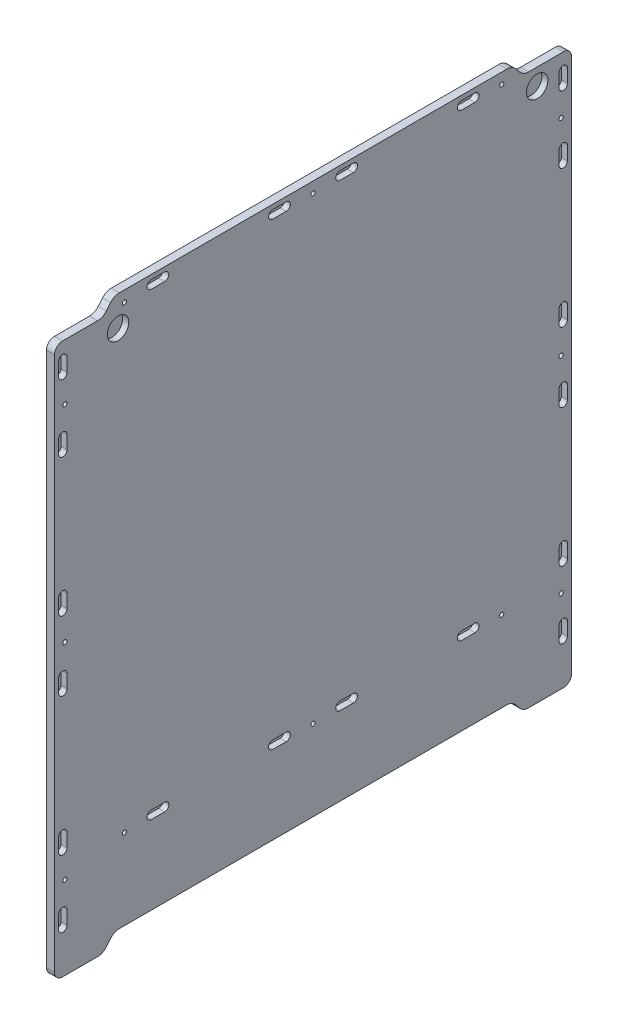
SolidWorks part; units mm, degrees
ref_plane "Alzado" through (0, 0, 0) normal (0, 0, 1) x (1, 0, 0)
ref_plane "Planta" through (0, 0, 0) normal (0, 1, 0) x (1, 0, 0)
ref_plane "Vista lateral" through (0, 0, 0) normal (1, 0, 0) x (0, 0, -1)
sketch "Croquis1" plane through (0, 0, 0) normal (1, 0, 0) x (0, 0, -1)
  line L0 (-15.4032, 213.9092) -> (-15.4032, -196.0905) construction
  line L1 (138.549, -203.0545) -> (135.2533, -199.1268)
  line L2 (171.0968, -206.0908) -> (145.0604, -206.0908)
  line L3 (177.0968, 198.0069) -> (177.0968, -200.0908)
  line L4 (145.0968, 204.0069) -> (171.0968, 204.0069)
  line L5 (-159.667, 213.9092) -> (128.8605, 213.9092)
  line L6 (-166.1784, 210.8729) -> (-169.3918, 207.0432)
  line L7 (-175.9032, 204.0069) -> (-201.9032, 204.0069)
  line L8 (-207.9032, 198.0069) -> (-207.9032, -200.0908)
  line L9 (-201.9032, -206.0908) -> (-175.8668, -206.0908)
  line L10 (-169.3555, -203.0545) -> (-166.0597, -199.1268)
  line L11 (-159.5483, -196.0905) -> (128.7419, -196.0905)
  line L12 (135.3719, 210.8729) -> (138.5854, 207.0432)
  line L21 (-207.9032, 8.9094) -> (177.0968, 8.9094) construction
  arc A0 (128.7419, -196.0905) -> (135.2533, -199.1268) centre (128.7419, -204.5905) cw
  arc A1 (145.0604, -206.0908) -> (138.549, -203.0545) centre (145.0604, -197.5908) cw
  arc A2 (177.0968, -200.0908) -> (171.0968, -206.0908) centre (171.0968, -200.0908) cw
  arc A3 (171.0968, 204.0069) -> (177.0968, 198.0069) centre (171.0968, 198.0069) cw
  arc A4 (145.0968, 204.0069) -> (138.5854, 207.0432) centre (145.0968, 212.5069) cw
  arc A5 (-159.667, 213.9092) -> (-166.1784, 210.8729) centre (-159.667, 205.4092) ccw
  arc A6 (-175.9032, 204.0069) -> (-169.3918, 207.0432) centre (-175.9032, 212.5069) ccw
  arc A7 (-201.9032, 204.0069) -> (-207.9032, 198.0069) centre (-201.9032, 198.0069) ccw
  arc A8 (-207.9032, -200.0908) -> (-201.9032, -206.0908) centre (-201.9032, -200.0908) ccw
  arc A9 (-175.8668, -206.0908) -> (-169.3555, -203.0545) centre (-175.8668, -197.5908) ccw
  arc A10 (-159.5483, -196.0905) -> (-166.0597, -199.1268) centre (-159.5483, -204.5905) ccw
  arc A11 (128.8605, 213.9092) -> (135.3719, 210.8729) centre (128.8605, 205.4092) cw
  circle A12 centre (151.4968, 191.5069) radius 4.25
  circle A13 centre (-160.6032, 191.5069) radius 4.25
  circle A22 centre (-15.4032, 205.9092) radius 1.55
  circle A23 centre (125.0968, 205.9092) radius 1.55
  circle A24 centre (-155.9032, 205.9092) radius 1.55
  circle A25 centre (-15.4032, -136.0908) radius 1.55
  circle A26 centre (125.0968, -136.0908) radius 1.55
  circle A27 centre (-155.9032, -136.0908) radius 1.55
  circle A28 centre (-200.1532, 162.2069) radius 1.6
  circle A29 centre (-200.1532, 8.9094) radius 1.6
  circle A30 centre (-200.1532, -144.3882) radius 1.6
  circle A31 centre (169.3468, -144.3882) radius 1.6
  circle A32 centre (169.3468, 8.9094) radius 1.6
  circle A33 centre (169.3468, 162.2069) radius 1.6
  point P42 (-15.4032, 8.9094)
  dimension "D3" = 15.9023
  dimension "D6" = 25.6
  dimension "D8" = 47.3
  dimension "D4" = 8.5
  dimension "D12" = 41.8
  dimension "D13" = 52
  dimension "D14" = 52
  dimension "D15" = 7.75
  dimension "D16" = 52
  dimension "D17" = 52
  dimension "D22" = 6
  dimension "D23" = 6
  dimension "D25" = 8.5
  dimension "D26" = 8.5
  dimension "D27" = 50
  dimension "D29" = 8.5
  dimension "D30" = 8.5
  dimension "D33" = 3.2
  dimension "D34" = 3.2
  dimension "D18" = 7.75
  dimension "D21" = 10.0003
  dimension "D28" = 32.0364
  dimension "D31" = 32
  dimension "D32" = 50
extrude "Saliente-Extruir1" add sketch "Croquis1" along normal blind 6
sketch "Croquis3" plane through (6, 0, 0) normal (1, 0, 0) x (0, 0, -1)
  line L0 (-15.4032, 213.9092) -> (-15.4032, -196.0905) construction
  line L1 (128.8605, 213.9092) -> (-159.667, 213.9092) construction
  line L2 (-159.5483, -196.0905) -> (128.7419, -196.0905) construction
  line L5 (-198.6032, 192.2069) -> (-198.6032, 182.2069)
  line L6 (-204.8032, 192.2069) -> (-204.8032, 182.2069)
  line L7 (-175.9032, 204.0069) -> (-201.9032, 204.0069) construction
  line L8 (-207.9032, 198.0069) -> (-207.9032, -200.0908) construction
  line L9 (-198.6032, 142.2069) -> (-198.6032, 132.2069)
  line L10 (-204.8032, 142.2069) -> (-204.8032, 132.2069)
  line L11 (177.0968, 8.9094) -> (-207.9032, 8.9094) construction
  line L12 (177.0968, -200.0908) -> (177.0968, 198.0069) construction
  line L13 (-198.6032, -124.3882) -> (-198.6032, -114.3882)
  line L14 (-204.8032, -124.3882) -> (-204.8032, -114.3882)
  line L15 (-204.8032, -174.3882) -> (-204.8032, -164.3882)
  line L16 (-198.6032, -174.3882) -> (-198.6032, -164.3882)
  line L17 (-15.4032, 8.9094) -> (-15.4032, 213.9092) construction
  line L19 (-201.7032, 179.1069) -> (-201.7032, 145.3069) construction
  line L20 (-198.6032, 39.7671) -> (-198.6032, 29.7671)
  line L21 (-204.8032, 39.7671) -> (-204.8032, 29.7671)
  line L22 (-198.6032, -11.9484) -> (-198.6032, -21.9484)
  line L23 (-204.8032, -11.9484) -> (-204.8032, -21.9484)
  line L24 (-201.7032, 26.6671) -> (-201.7032, -8.8484) construction
  line L25 (167.7968, -174.3882) -> (167.7968, -164.3882)
  line L26 (173.9968, -174.3882) -> (173.9968, -164.3882)
  line L27 (173.9968, -124.3882) -> (173.9968, -114.3882)
  line L28 (167.7968, -124.3882) -> (167.7968, -114.3882)
  line L29 (173.9968, -11.9484) -> (173.9968, -21.9484)
  line L30 (167.7968, -11.9484) -> (167.7968, -21.9484)
  line L31 (173.9968, 39.7671) -> (173.9968, 29.7671)
  line L32 (-45.4032, 210.5092) -> (-35.4032, 210.5092)
  line L33 (-45.4032, 204.3092) -> (-35.4032, 204.3092)
  line L34 (-135.9032, 210.5092) -> (-125.9032, 210.5092)
  line L35 (-135.9032, 204.3092) -> (-125.9032, 204.3092)
  line L36 (167.7968, 39.7671) -> (167.7968, 29.7671)
  line L37 (105.0968, 204.3092) -> (95.0968, 204.3092)
  line L38 (105.0968, 210.5092) -> (95.0968, 210.5092)
  line L39 (14.5968, 204.3092) -> (4.5968, 204.3092)
  line L40 (14.5968, 210.5092) -> (4.5968, 210.5092)
  line L41 (-135.9032, -131.4908) -> (-125.9032, -131.4908)
  line L42 (-135.9032, -137.6908) -> (-125.9032, -137.6908)
  line L43 (-45.4032, -131.4908) -> (-35.4032, -131.4908)
  line L44 (-45.4032, -137.6908) -> (-35.4032, -137.6908)
  line L45 (14.5968, -131.4908) -> (4.5968, -131.4908)
  line L46 (14.5968, -137.6908) -> (4.5968, -137.6908)
  line L47 (105.0968, -131.4908) -> (95.0968, -131.4908)
  line L48 (105.0968, -137.6908) -> (95.0968, -137.6908)
  line L49 (-135.9032, 210.5092) -> (-135.9032, -131.4908) construction
  line L50 (173.9968, 142.2069) -> (173.9968, 132.2069)
  line L51 (167.7968, 142.2069) -> (167.7968, 132.2069)
  line L52 (173.9968, 192.2069) -> (173.9968, 182.2069)
  line L53 (167.7968, 192.2069) -> (167.7968, 182.2069)
  circle A0 centre (-160.6032, 191.5069) radius 8
  circle A1 centre (151.4968, 191.5069) radius 8
  arc A4 (-198.6032, 192.2069) -> (-204.8032, 192.2069) centre (-201.7032, 192.2069) ccw
  arc A5 (-204.8032, 182.2069) -> (-198.6032, 182.2069) centre (-201.7032, 182.2069) ccw
  arc A6 (-198.6032, 142.2069) -> (-204.8032, 142.2069) centre (-201.7032, 142.2069) ccw
  arc A7 (-204.8032, 132.2069) -> (-198.6032, 132.2069) centre (-201.7032, 132.2069) ccw
  arc A8 (-204.8032, -114.3882) -> (-198.6032, -114.3882) centre (-201.7032, -114.3882) cw
  arc A9 (-198.6032, -124.3882) -> (-204.8032, -124.3882) centre (-201.7032, -124.3882) cw
  arc A10 (-204.8032, -164.3882) -> (-198.6032, -164.3882) centre (-201.7032, -164.3882) cw
  arc A11 (-198.6032, -174.3882) -> (-204.8032, -174.3882) centre (-201.7032, -174.3882) cw
  arc A12 (-198.6032, 39.7671) -> (-204.8032, 39.7671) centre (-201.7032, 39.7671) ccw
  arc A13 (-204.8032, 29.7671) -> (-198.6032, 29.7671) centre (-201.7032, 29.7671) ccw
  arc A14 (-198.6032, -11.9484) -> (-204.8032, -11.9484) centre (-201.7032, -11.9484) ccw
  arc A15 (-204.8032, -21.9484) -> (-198.6032, -21.9484) centre (-201.7032, -21.9484) ccw
  arc A16 (167.7968, -174.3882) -> (173.9968, -174.3882) centre (170.8968, -174.3882) ccw
  arc A17 (173.9968, -164.3882) -> (167.7968, -164.3882) centre (170.8968, -164.3882) ccw
  arc A18 (167.7968, -124.3882) -> (173.9968, -124.3882) centre (170.8968, -124.3882) ccw
  arc A19 (173.9968, -114.3882) -> (167.7968, -114.3882) centre (170.8968, -114.3882) ccw
  arc A20 (173.9968, -21.9484) -> (167.7968, -21.9484) centre (170.8968, -21.9484) cw
  arc A21 (167.7968, -11.9484) -> (173.9968, -11.9484) centre (170.8968, -11.9484) cw
  arc A22 (173.9968, 29.7671) -> (167.7968, 29.7671) centre (170.8968, 29.7671) cw
  arc A23 (167.7968, 39.7671) -> (173.9968, 39.7671) centre (170.8968, 39.7671) cw
  arc A24 (173.9968, 132.2069) -> (167.7968, 132.2069) centre (170.8968, 132.2069) cw
  arc A25 (167.7968, 142.2069) -> (173.9968, 142.2069) centre (170.8968, 142.2069) cw
  arc A26 (173.9968, 182.2069) -> (167.7968, 182.2069) centre (170.8968, 182.2069) cw
  arc A27 (167.7968, 192.2069) -> (173.9968, 192.2069) centre (170.8968, 192.2069) cw
  arc A28 (-35.4032, 204.3092) -> (-35.4032, 210.5092) centre (-35.4032, 207.4092) ccw
  arc A29 (-45.4032, 210.5092) -> (-45.4032, 204.3092) centre (-45.4032, 207.4092) ccw
  arc A30 (-125.9032, 204.3092) -> (-125.9032, 210.5092) centre (-125.9032, 207.4092) ccw
  arc A31 (-135.9032, 210.5092) -> (-135.9032, 204.3092) centre (-135.9032, 207.4092) ccw
  arc A32 (105.0968, 210.5092) -> (105.0968, 204.3092) centre (105.0968, 207.4092) cw
  arc A33 (95.0968, 204.3092) -> (95.0968, 210.5092) centre (95.0968, 207.4092) cw
  arc A34 (14.5968, 210.5092) -> (14.5968, 204.3092) centre (14.5968, 207.4092) cw
  arc A35 (4.5968, 204.3092) -> (4.5968, 210.5092) centre (4.5968, 207.4092) cw
  arc A36 (-125.9032, -137.6908) -> (-125.9032, -131.4908) centre (-125.9032, -134.5908) ccw
  arc A37 (-135.9032, -131.4908) -> (-135.9032, -137.6908) centre (-135.9032, -134.5908) ccw
  arc A38 (-35.4032, -137.6908) -> (-35.4032, -131.4908) centre (-35.4032, -134.5908) ccw
  arc A39 (-45.4032, -131.4908) -> (-45.4032, -137.6908) centre (-45.4032, -134.5908) ccw
  arc A40 (14.5968, -131.4908) -> (14.5968, -137.6908) centre (14.5968, -134.5908) cw
  arc A41 (4.5968, -137.6908) -> (4.5968, -131.4908) centre (4.5968, -134.5908) cw
  arc A42 (105.0968, -131.4908) -> (105.0968, -137.6908) centre (105.0968, -134.5908) cw
  arc A43 (95.0968, -137.6908) -> (95.0968, -131.4908) centre (95.0968, -134.5908) cw
  circle A44 centre (-155.9032, 205.9092) radius 1.55 construction
  circle A45 centre (-155.9032, 205.9092) radius 1.55 construction
  dimension "D2" = 16
  dimension "D5" = 10
  dimension "D10" = 10
  dimension "D15" = 3.1
  dimension "D17" = 3.1
  dimension "D3" = 16
  dimension "D6" = 11.8
  dimension "D7" = 6.2
  dimension "D11" = 20
  dimension "D12" = 6.5
  dimension "D16" = 20
  dimension "D9" = 10
  dimension "D18" = 6.2
  dimension "D8" = 2
  dimension "D13" = 2
  dimension "D14" = 2
extrude "Cortar-Extruir1" cut sketch "Croquis3" against normal blind 4.5
chamfer "Chaflán1" distance 1.5 angle 45 12 edges at (0, 205.9092, 13.8532) (0, 205.9092, -126.6468) (0, -136.0908, -126.6468) (0, -136.0908, 13.8532) (0, -136.0908, 154.3532) (0, 162.2069, 198.5532) (0, 205.9092, 154.3532) (0, 162.2069, -167.7468) (0, 8.9094, -167.7468) (0, -144.3882, -170.9468) (0, -144.3882, 201.7532) (0, 8.9094, 198.5532)
sketch "Croquis4" plane through (0, 0, 0) normal (-1, 0, 0) x (0, 0, 1)
  line L1 (-146.0451, 197.286) -> (-157.1453, 197.286)
  line L2 (-146.0451, 197.286) -> (-146.0451, 186.0138)
  line L3 (-146.0451, 186.0138) -> (-157.1453, 186.0138)
  line L4 (-157.1453, 197.286) -> (-157.1453, 186.0138)
  line L5 (166.7347, 197.286) -> (154.7354, 197.286)
  line L6 (166.7347, 197.286) -> (166.7347, 186.0138)
  line L7 (166.7347, 186.0138) -> (154.7354, 186.0138)
  line L8 (154.7354, 197.286) -> (154.7354, 186.0138)
extrude "Saliente-Extruir2" add sketch "Croquis4" against normal blind 1.5
equation "\"Ancho_panel\"= 385'Ancho del panel"
equation "\"Alto_panel\"= 420'Alto del panel izquierdo"
equation "\"Altura_base_taladros\"= 70'Alto taladros de la base eje Z"
equation "\"Altura_superior_taladros\"= 8mm'Distancia taladros a top"
equation "\"Distancia_vert_entre_horizontales_ensambles\"= \"Alto_panel\" - \"Altura_base_taladros\" - \"Altura_superior_taladros\"'Distancia vertical entre horizontales de ensambles"
equation "\"Latrales_separacion_barras_a_escalon_bajo\"= 12.5'Separación entre las barras y el escalón inferior de la parte superior"
equation "\"Espacio_tensor_correa_motor\"= 8.5mm'Espacio para mover el motor en vertical y tensar la correa"
